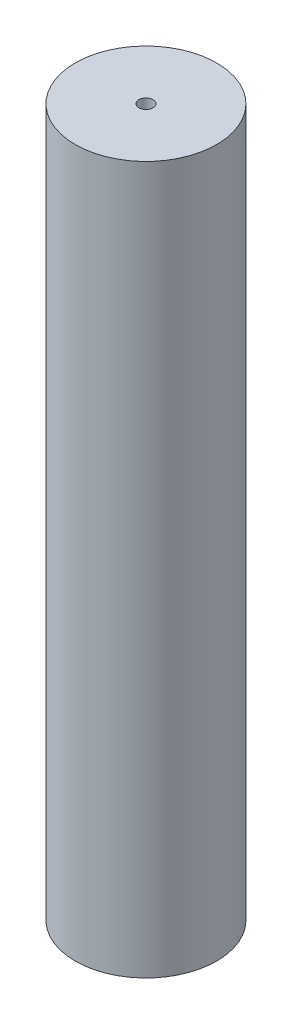
SolidWorks part; units mm, degrees
ref_plane "Front Plane" through (0, 0, 0) normal (0, 0, 1) x (1, 0, 0)
ref_plane "Top Plane" through (0, 0, 0) normal (0, 1, 0) x (1, 0, 0)
ref_plane "Right Plane" through (0, 0, 0) normal (1, 0, 0) x (0, 0, -1)
sketch "Sketch1" plane through (0, 0, 0) normal (0, 1, 0) x (1, 0, 0)
  line L0 (0, 0) -> (0, 65.5458) construction
  line L1 (0, 0) -> (-59.0385, 0) construction
  circle A0 centre (0, 0) radius 100
  circle A1 centre (0, 0) radius 10
  dimension "D1" = 200
  dimension "D2" = 20
extrude "Boss-Extrude1" add sketch "Sketch1" along normal blind 1000
